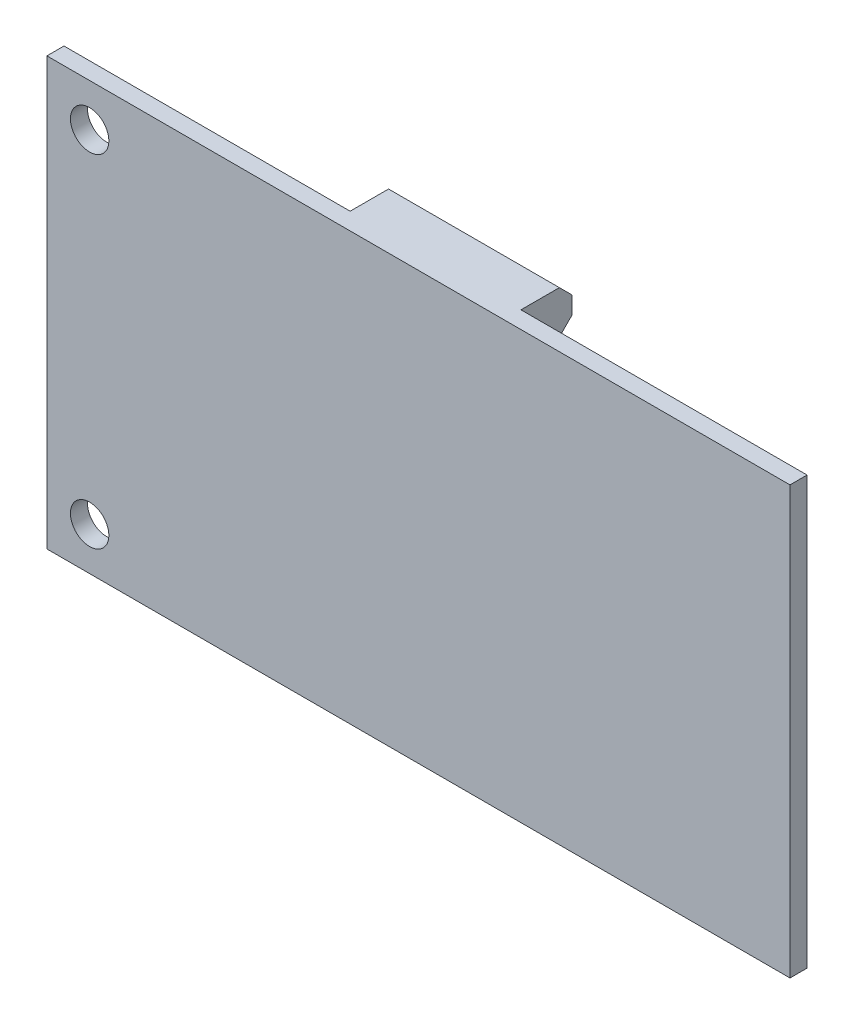
SolidWorks part; units mm, degrees
ref_plane "Front Plane" through (0, 0, 0) normal (0, 0, 1) x (1, 0, 0)
ref_plane "Top Plane" through (0, 0, 0) normal (0, 1, 0) x (1, 0, 0)
ref_plane "Right Plane" through (0, 0, 0) normal (1, 0, 0) x (0, 0, -1)
sketch "Sketch1" plane through (0, 0, 0) normal (0, 0, 1) x (1, 0, 0)
  line L1 (43.5, -25) -> (-43.5, -25)
  line L2 (43.5, -25) -> (43.5, 25)
  line L3 (43.5, 25) -> (-43.5, 25)
  line L4 (-43.5, -25) -> (-43.5, 25)
  line L5 (43.5, -25) -> (-43.5, 25) construction
  line L6 (43.5, 25) -> (-43.5, -25) construction
  point P0 (0, 0)
  dimension "D1" = 50
  dimension "D2" = 87
extrude "Boss-Extrude1" add sketch "Sketch1" along normal blind 2
sketch "Sketch3" plane through (0, 25, 0) normal (0, 1, 0) x (1, 0, 0)
  line L0 (43.5, 0) -> (-43.5, 0) construction
  line L1 (-10, 0) -> (10, 0)
  line L2 (-10, 0) -> (-10, 6)
  line L3 (-10, 6) -> (10, 6)
  line L4 (10, 0) -> (10, 6)
  point P6 (0, 0)
  dimension "D1" = 6
  dimension "D2" = 20
extrude "Boss-Extrude2" add sketch "Sketch3" against normal blind 5
chamfer "Chamfer1" distance 1.5 angle 45 2 edges at (0, 20, -6) (0, 25, -6)
sketch "Sketch4" plane through (0, -25, 0) normal (0, -1, 0) x (1, 0, 0)
  line L0 (-43.5, 0) -> (43.5, 0) construction
  line L1 (-10, 0) -> (-20, 0)
  line L2 (-10, 0) -> (-10, -6)
  line L3 (-10, -6) -> (-20, -6)
  line L4 (-20, 0) -> (-20, -6)
  line L5 (-10, -4.5) -> (-10, 0) construction
  dimension "D1" = 10
  dimension "D2" = 6
extrude "Boss-Extrude3" add sketch "Sketch4" against normal blind 5
chamfer "Chamfer2" distance 1.5 angle 45 2 edges at (-15, -20, -6) (-15, -25, -6)
sketch "Sketch5" plane through (0, 0, 0) normal (0, 0, -1) x (-1, 0, 0)
  line L0 (10, -25) -> (-43.5, -25) construction
  line L1 (-23.5, -25) -> (-16.5, -25)
  line L2 (-23.5, -25) -> (-23.5, -22.5)
  line L3 (-23.5, -22.5) -> (-16.5, -22.5)
  line L4 (-16.5, -25) -> (-16.5, -22.5)
  line L5 (-43.5, -25) -> (-43.5, 25) construction
  dimension "D1" = 2.5
  dimension "D2" = 7
  dimension "D3" = 20
extrude "Boss-Extrude4" add sketch "Sketch5" along normal blind 6
sketch "Sketch8" plane through (0, 0, 2) normal (0, 0, 1) x (1, 0, 0)
  circle A1 centre (-38.5, -20) radius 1.65 construction
  circle A2 centre (-38.5, 20) radius 1.65 construction
  point P0 (-38.5, -20)
  point P9 (-38.5, 20)
hole_wizard "M4 Clearance Hole1" positions "Sketch9" profile "Sketch10" hole size "M4" standard "ANSI Metric" end condition up to next
sketch "Sketch9" plane through (0, 0, 0) normal (0, 0, -1) x (-1, 0, 0)
  circle A0 centre (38.5, 20) radius 1.65 construction
  point P0 (38.5, -20)
  point P4 (38.5, 20)
sketch "Sketch10" plane through (-38.5, -20, 0) normal (1, 0, 0) x (0, 1, 0)
  line L0 (0, 0) -> (0, 2)
  line L1 (0, 2) -> (2.25, 2)
  line L2 (2.25, 2) -> (2.25, 0)
  line L5 (2.25, 0) -> (0, 0)
  line L11 (0, -6.35) -> (0, 107.95) construction
  dimension "Thru Hole Dia." = 4.5
  dimension "Thru Hole Depth" = 2
